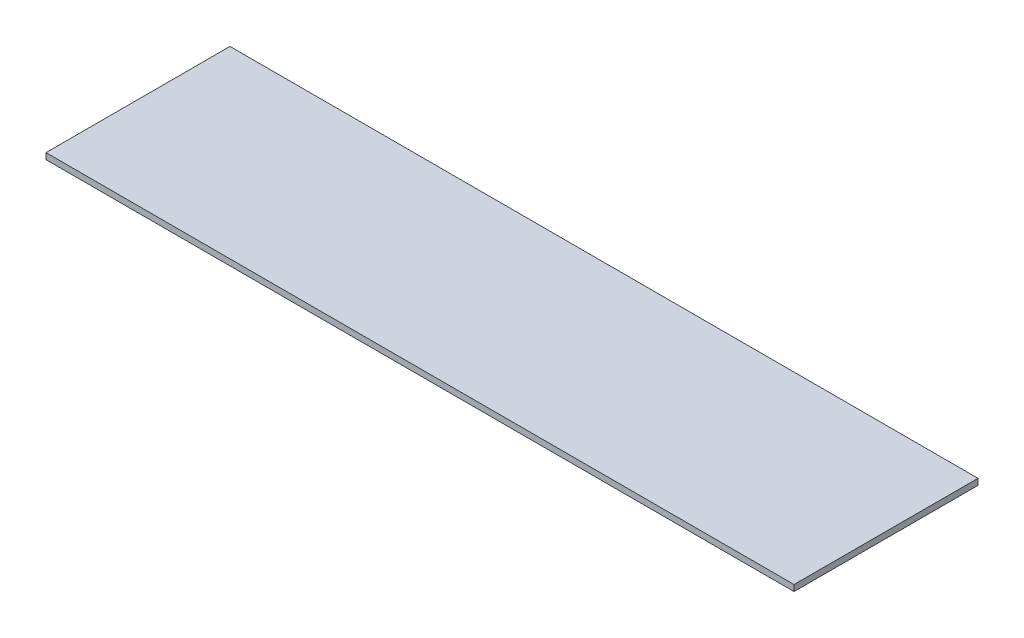
SolidWorks part; units mm, degrees
ref_plane "Front Plane" through (0, 0, 0) normal (0, 0, 1) x (1, 0, 0)
ref_plane "Top Plane" through (0, 0, 0) normal (0, 1, 0) x (1, 0, 0)
ref_plane "Right Plane" through (0, 0, 0) normal (1, 0, 0) x (0, 0, -1)
sketch "Sketch1" plane through (0, 0, 0) normal (0, 1, 0) x (1, 0, 0)
  line L0 (0, 88.9) -> (0, -88.9) construction
  line L1 (-381, 88.9) -> (381, 88.9)
  line L2 (-381, 88.9) -> (-381, -88.9)
  line L3 (-381, -88.9) -> (381, -88.9)
  line L4 (381, 88.9) -> (381, -88.9)
  line L5 (-381, 39.4607) -> (-381, 65.7679)
  line L7 (-381, 65.7679) -> (-381, 88.9)
  line L14 (-325.0712, -88.9) -> (-381, -88.9)
  line L19 (381, 65.7679) -> (381, 88.9)
  line L22 (-325.0712, 88.9) -> (-381, 88.9)
  line L29 (381, 39.4607) -> (381, 65.7679)
  line L33 (-381, 13.1536) -> (-381, 39.4607)
  line L37 (381, 13.1536) -> (381, 39.4607)
  line L41 (-381, -13.1536) -> (-381, 13.1536)
  line L45 (381, -13.1536) -> (381, 13.1536)
  line L49 (-381, -39.4607) -> (-381, -13.1536)
  line L53 (381, -39.4607) -> (381, -13.1536)
  line L57 (-381, -65.7679) -> (-381, -39.4607)
  line L61 (381, -65.7679) -> (381, -39.4607)
  line L65 (-381, -88.9) -> (-381, -65.7679)
  line L69 (381, -88.9) -> (381, -65.7679)
  line L74 (-265.9673, -88.9) -> (-325.0712, -88.9)
  line L78 (-265.9673, 88.9) -> (-325.0712, 88.9)
  line L82 (-206.8635, -88.9) -> (-265.9673, -88.9)
  line L86 (-206.8635, 88.9) -> (-265.9673, 88.9)
  line L90 (-147.7596, -88.9) -> (-206.8635, -88.9)
  line L93 (-147.7596, 88.9) -> (-147.7596, 92.075)
  line L94 (-147.7596, 88.9) -> (-206.8635, 88.9)
  line L98 (-88.6558, -88.9) -> (-147.7596, -88.9)
  line L102 (-88.6558, 88.9) -> (-147.7596, 88.9)
  line L103 (-147.7596, 88.9) -> (-147.7596, 92.075)
  line L105 (-29.5519, -88.9) -> (-29.5519, -92.075)
  line L106 (-29.5519, -88.9) -> (-88.6558, -88.9)
  line L110 (-29.5519, 88.9) -> (-88.6558, 88.9)
  line L114 (29.5519, -88.9) -> (-29.5519, -88.9)
  line L115 (-29.5519, -88.9) -> (-29.5519, -92.075)
  line L118 (29.5519, 88.9) -> (-29.5519, 88.9)
  line L122 (88.6558, -88.9) -> (29.5519, -88.9)
  line L126 (88.6558, 88.9) -> (29.5519, 88.9)
  line L130 (147.7596, -88.9) -> (88.6558, -88.9)
  line L134 (147.7596, 88.9) -> (88.6558, 88.9)
  line L138 (206.8635, -88.9) -> (147.7596, -88.9)
  line L142 (206.8635, 88.9) -> (147.7596, 88.9)
  line L146 (265.9673, -88.9) -> (206.8635, -88.9)
  line L150 (265.9673, 88.9) -> (206.8635, 88.9)
  line L186 (325.0712, -88.9) -> (265.9673, -88.9)
  line L190 (325.0712, 88.9) -> (265.9673, 88.9)
  line L194 (381, -88.9) -> (325.0712, -88.9)
  line L198 (381, 88.9) -> (325.0712, 88.9)
  point P8 (0, 88.9)
  point P9 (0, 0)
  dimension "D1" = 762
  dimension "D2" = 177.8
  dimension "D4" = 7
  dimension "D7" = 13
extrude "Boss-Extrude1" add sketch "Sketch1" along normal blind 6.35
sketch "Sketch4" [suppressed] plane through (0, 0, 0) normal (0, 1, 0) x (1, 0, 0)
  line L0 (0.0158, 88.9) -> (0.0158, -88.9) construction
  line L1 (-380.9842, 88.9) -> (381.0158, 88.9)
  line L2 (-380.9842, 88.9) -> (-380.9842, -88.9)
  line L3 (-380.9842, -88.9) -> (381.0158, -88.9)
  line L4 (381.0158, 88.9) -> (381.0158, -88.9)
  line L5 (-381, 39.4607) -> (-381, 65.7679)
  line L6 (-380.9842, 65.7679) -> (-384.1592, 65.7679)
  line L7 (-380.9842, 65.7679) -> (-380.9842, 92.075)
  line L8 (-380.9842, 92.075) -> (-384.1592, 92.075)
  line L9 (-384.1592, 65.7679) -> (-384.1592, 92.075)
  line L10 (-325.0554, -88.9) -> (-384.1592, -88.9)
  line L11 (-325.0554, -88.9) -> (-325.0554, -92.075)
  line L12 (-325.0554, -92.075) -> (-384.1592, -92.075)
  line L13 (-384.1592, -88.9) -> (-384.1592, -92.075)
  line L14 (381.0158, 65.7679) -> (384.1908, 65.7679)
  line L15 (381.0158, 65.7679) -> (381.0158, 92.075)
  line L16 (381.0158, 92.075) -> (384.1908, 92.075)
  line L17 (384.1908, 65.7679) -> (384.1908, 92.075)
  line L18 (-325.0554, 88.9) -> (-384.1592, 88.9)
  line L19 (-325.0554, 88.9) -> (-325.0554, 92.075)
  line L20 (-325.0554, 92.075) -> (-384.1592, 92.075)
  line L21 (-384.1592, 88.9) -> (-384.1592, 92.075)
  line L22 (-381, 39.4607) -> (-384.175, 39.4607)
  line L23 (-384.175, 39.4607) -> (-384.1592, 65.7679)
  line L24 (-381, 65.7679) -> (-384.1592, 65.7679)
  line L25 (381, 39.4607) -> (381, 65.7679)
  line L26 (381, 39.4607) -> (384.175, 39.4607)
  line L27 (384.175, 39.4607) -> (384.175, 65.7679)
  line L28 (381, 65.7679) -> (384.175, 65.7679)
  line L29 (-381, 13.1536) -> (-381, 39.4607)
  line L30 (-381, 13.1536) -> (-384.175, 13.1536)
  line L31 (-384.175, 13.1536) -> (-384.175, 39.4607)
  line L32 (-381, 39.4607) -> (-384.175, 39.4607)
  line L33 (381, 13.1536) -> (381, 39.4607)
  line L34 (381, 13.1536) -> (384.175, 13.1536)
  line L35 (384.175, 13.1536) -> (384.175, 39.4607)
  line L36 (381, 39.4607) -> (384.175, 39.4607)
  line L37 (-381, -13.1536) -> (-381, 13.1536)
  line L38 (-381, -13.1536) -> (-384.175, -13.1536)
  line L39 (-384.175, -13.1536) -> (-384.175, 13.1536)
  line L40 (-381, 13.1536) -> (-384.175, 13.1536)
  line L41 (381, -13.1536) -> (381, 13.1536)
  line L42 (381, -13.1536) -> (384.175, -13.1536)
  line L43 (384.175, -13.1536) -> (384.175, 13.1536)
  line L44 (381, 13.1536) -> (384.175, 13.1536)
  line L45 (-381, -39.4607) -> (-381, -13.1536)
  line L46 (-381, -39.4607) -> (-384.175, -39.4607)
  line L47 (-384.175, -39.4607) -> (-384.175, -13.1536)
  line L48 (-381, -13.1536) -> (-384.175, -13.1536)
  line L49 (381, -39.4607) -> (381, -13.1536)
  line L50 (381, -39.4607) -> (384.175, -39.4607)
  line L51 (384.175, -39.4607) -> (384.175, -13.1536)
  line L52 (381, -13.1536) -> (384.175, -13.1536)
  line L53 (-381, -65.7679) -> (-381, -39.4607)
  line L54 (-381, -65.7679) -> (-384.175, -65.7679)
  line L55 (-384.175, -65.7679) -> (-384.175, -39.4607)
  line L56 (-381, -39.4607) -> (-384.175, -39.4607)
  line L57 (381, -65.7679) -> (381, -39.4607)
  line L58 (381, -65.7679) -> (384.175, -65.7679)
  line L59 (384.175, -65.7679) -> (384.175, -39.4607)
  line L60 (381, -39.4607) -> (384.175, -39.4607)
  line L61 (-381, -92.075) -> (-381, -65.7679)
  line L62 (-381, -92.075) -> (-384.175, -92.075)
  line L63 (-384.175, -92.075) -> (-384.175, -65.7679)
  line L64 (-381, -65.7679) -> (-384.175, -65.7679)
  line L65 (381, -92.075) -> (381, -65.7679)
  line L66 (381, -92.075) -> (384.175, -92.075)
  line L67 (384.175, -92.075) -> (384.175, -65.7679)
  line L68 (381, -65.7679) -> (384.175, -65.7679)
  line L69 (-265.9673, -88.9) -> (-265.9673, -92.075)
  line L70 (-265.9673, -88.9) -> (-325.0554, -88.9)
  line L71 (-325.0554, -88.9) -> (-325.0554, -92.075)
  line L72 (-265.9673, -92.075) -> (-325.0554, -92.075)
  line L73 (-265.9673, 88.9) -> (-265.9673, 92.075)
  line L74 (-265.9673, 88.9) -> (-325.0712, 88.9)
  line L75 (-325.0712, 88.9) -> (-325.0712, 92.075)
  line L76 (-265.9673, 92.075) -> (-325.0712, 92.075)
  line L77 (-206.8635, -88.9) -> (-206.8635, -92.075)
  line L78 (-206.8635, -88.9) -> (-265.9673, -88.9)
  line L79 (-265.9673, -88.9) -> (-265.9673, -92.075)
  line L80 (-206.8635, -92.075) -> (-265.9673, -92.075)
  line L81 (-206.8635, 88.9) -> (-206.8635, 92.075)
  line L82 (-206.8635, 88.9) -> (-265.9673, 88.9)
  line L83 (-265.9673, 88.9) -> (-265.9673, 92.075)
  line L84 (-206.8635, 92.075) -> (-265.9673, 92.075)
  line L85 (-147.7596, -88.9) -> (-147.7596, -92.075)
  line L86 (-147.7596, -88.9) -> (-206.8635, -88.9)
  line L87 (-206.8635, -88.9) -> (-206.8635, -92.075)
  line L88 (-147.7596, -92.075) -> (-206.8635, -92.075)
  line L89 (-147.7596, 88.9) -> (-147.7596, 92.075)
  line L90 (-147.7596, 88.9) -> (-206.8635, 88.9)
  line L91 (-206.8635, 88.9) -> (-206.8635, 92.075)
  line L92 (-147.7596, 92.075) -> (-206.8635, 92.075)
  line L93 (-88.6558, -88.9) -> (-88.6558, -92.075)
  line L94 (-88.6558, -88.9) -> (-147.7596, -88.9)
  line L95 (-147.7596, -88.9) -> (-147.7596, -92.075)
  line L96 (-88.6558, -92.075) -> (-147.7596, -92.075)
  line L97 (-88.6558, 88.9) -> (-88.6558, 92.075)
  line L98 (-88.6558, 88.9) -> (-147.7596, 88.9)
  line L99 (-147.7596, 88.9) -> (-147.7596, 92.075)
  line L100 (-88.6558, 92.075) -> (-147.7596, 92.075)
  line L101 (-29.5519, -88.9) -> (-29.5519, -92.075)
  line L102 (-29.5519, -88.9) -> (-88.6558, -88.9)
  line L103 (-88.6558, -88.9) -> (-88.6558, -92.075)
  line L104 (-29.5519, -92.075) -> (-88.6558, -92.075)
  line L105 (-29.5519, 88.9) -> (-29.5519, 92.075)
  line L106 (-29.5519, 88.9) -> (-88.6558, 88.9)
  line L107 (-88.6558, 88.9) -> (-88.6558, 92.075)
  line L108 (-29.5519, 92.075) -> (-88.6558, 92.075)
  line L109 (29.5519, -88.9) -> (29.5519, -92.075)
  line L110 (29.5519, -88.9) -> (-29.5519, -88.9)
  line L111 (-29.5519, -88.9) -> (-29.5519, -92.075)
  line L112 (29.5519, -92.075) -> (-29.5519, -92.075)
  line L113 (29.5519, 88.9) -> (29.5519, 92.075)
  line L114 (29.5519, 88.9) -> (-29.5519, 88.9)
  line L115 (-29.5519, 88.9) -> (-29.5519, 92.075)
  line L116 (29.5519, 92.075) -> (-29.5519, 92.075)
  line L117 (88.6558, -88.9) -> (88.6558, -92.075)
  line L118 (88.6558, -88.9) -> (29.5519, -88.9)
  line L119 (29.5519, -88.9) -> (29.5519, -92.075)
  line L120 (88.6558, -92.075) -> (29.5519, -92.075)
  line L121 (88.6558, 88.9) -> (88.6558, 92.075)
  line L122 (88.6558, 88.9) -> (29.5519, 88.9)
  line L123 (29.5519, 88.9) -> (29.5519, 92.075)
  line L124 (88.6558, 92.075) -> (29.5519, 92.075)
  line L125 (147.7596, -88.9) -> (147.7596, -92.075)
  line L126 (147.7596, -88.9) -> (88.6558, -88.9)
  line L127 (88.6558, -88.9) -> (88.6558, -92.075)
  line L128 (147.7596, -92.075) -> (88.6558, -92.075)
  line L129 (147.7596, 88.9) -> (147.7596, 92.075)
  line L130 (147.7596, 88.9) -> (88.6558, 88.9)
  line L131 (88.6558, 88.9) -> (88.6558, 92.075)
  line L132 (147.7596, 92.075) -> (88.6558, 92.075)
  line L133 (206.8635, -88.9) -> (206.8635, -92.075)
  line L134 (206.8635, -88.9) -> (147.7596, -88.9)
  line L135 (147.7596, -88.9) -> (147.7596, -92.075)
  line L136 (206.8635, -92.075) -> (147.7596, -92.075)
  line L137 (206.8635, 88.9) -> (206.8635, 92.075)
  line L138 (206.8635, 88.9) -> (147.7596, 88.9)
  line L139 (147.7596, 88.9) -> (147.7596, 92.075)
  line L140 (206.8635, 92.075) -> (147.7596, 92.075)
  line L141 (265.9673, -88.9) -> (265.9673, -92.075)
  line L142 (265.9673, -88.9) -> (206.8635, -88.9)
  line L143 (206.8635, -88.9) -> (206.8635, -92.075)
  line L144 (265.9673, -92.075) -> (206.8635, -92.075)
  line L145 (265.9673, 88.9) -> (265.9673, 92.075)
  line L146 (265.9673, 88.9) -> (206.8635, 88.9)
  line L147 (206.8635, 88.9) -> (206.8635, 92.075)
  line L148 (265.9673, 92.075) -> (206.8635, 92.075)
  line L149 (325.0712, -88.9) -> (325.0712, -92.075)
  line L150 (325.0712, -88.9) -> (265.9673, -88.9)
  line L151 (265.9673, -88.9) -> (265.9673, -92.075)
  line L152 (325.0712, -92.075) -> (265.9673, -92.075)
  line L153 (325.0712, 88.9) -> (325.0712, 92.075)
  line L154 (325.0712, 88.9) -> (265.9673, 88.9)
  line L155 (265.9673, 88.9) -> (265.9673, 92.075)
  line L156 (325.0712, 92.075) -> (265.9673, 92.075)
  line L157 (384.175, -88.9) -> (384.175, -92.075)
  line L158 (384.175, -88.9) -> (325.0712, -88.9)
  line L159 (325.0712, -88.9) -> (325.0712, -92.075)
  line L160 (384.175, -92.075) -> (325.0712, -92.075)
  line L161 (384.175, 88.9) -> (384.175, 92.075)
  line L162 (384.175, 88.9) -> (325.0712, 88.9)
  line L163 (325.0712, 88.9) -> (325.0712, 92.075)
  line L164 (384.175, 92.075) -> (325.0712, 92.075)
  point P7 (0.0158, 88.9)
  dimension "D1" = 762
  dimension "D2" = 177.8
  dimension "D3" = 184.15
  dimension "D4" = 768.35
  dimension "D5" = 26.3071
  dimension "D6" = 59.1038
sketch "Sketch2" plane through (0, 6.35, 0) normal (0, 1, 0) x (1, 0, 0)
  line L0 (-123.825, 0) -> (123.825, 0) construction
  line L1 (-130.175, 15.4404) -> (-123.825, 15.4404) construction
  line L2 (-130.175, 15.4404) -> (-130.175, -15.4404) construction
  line L3 (-130.175, -15.4404) -> (-123.825, -15.4404) construction
  line L4 (-123.825, 15.4404) -> (-123.825, -15.4404) construction
  line L5 (123.825, 14.3164) -> (130.175, 14.3164) construction
  line L6 (123.825, 14.3164) -> (123.825, -14.3164) construction
  line L7 (123.825, -14.3164) -> (130.175, -14.3164) construction
  line L8 (130.175, 14.3164) -> (130.175, -14.3164) construction
  line L9 (-130.9687, 24.6215) -> (-123.0313, 24.6215) construction
  line L10 (-127, 24.6215) -> (-127, 15.4404) construction
  line L12 (-123.0312, 76.2) -> (-116.6812, 76.2)
  line L13 (-123.0312, 76.2) -> (-123.0313, 88.9)
  line L14 (-123.0313, 88.9) -> (-116.6812, 88.9)
  line L15 (-116.6812, 76.2) -> (-116.6812, 88.9)
  line L16 (-123.0313, 24.6215) -> (-123.0312, 76.2) construction
  line L18 (-116.6812, -88.9) -> (-123.0313, -88.9)
  line L19 (-116.6812, -88.9) -> (-116.6812, -76.2)
  line L20 (-116.6812, -76.2) -> (-123.0313, -76.2)
  line L21 (-123.0313, -88.9) -> (-123.0313, -76.2)
  line L31 (-381, 88.9) -> (381, 88.9) construction
  line L32 (-381, -88.9) -> (381, -88.9) construction
  line L33 (130.9688, 76.2) -> (130.9688, 88.9)
  line L34 (130.9688, 76.2) -> (137.3188, 76.2)
  line L35 (137.3188, 76.2) -> (137.3188, 88.9)
  line L36 (130.9688, 88.9) -> (137.3188, 88.9)
  line L37 (137.3188, -88.9) -> (137.3188, -76.2)
  line L38 (137.3188, -88.9) -> (130.9688, -88.9)
  line L39 (130.9688, -88.9) -> (130.9688, -76.2)
  line L40 (137.3188, -76.2) -> (130.9688, -76.2)
  line L41 (123.0313, 24.6215) -> (130.9688, 24.6215) construction
  line L42 (127, 24.6215) -> (127, 14.3164) construction
  line L43 (130.9688, 24.6215) -> (130.9688, 76.2) construction
  point P10 (0, 0)
  point P43 (127, 14.3164)
  dimension "D1" = 6.35
  dimension "D2" = 7.9375
  dimension "D4" = 6.35
  dimension "D5" = 12.7
  dimension "D3" = 254
  dimension "D6" = 2
extrude "Cut-Extrude1" [suppressed] cut sketch "Sketch2" against normal through all
sketch "Sketch5" plane through (0, 6.35, 0) normal (0, 1, 0) x (1, 0, 0)
  line L0 (-381, 88.9) -> (-381, -88.9) construction
  line L1 (-387.35, 95.25) -> (387.35, 95.25)
  line L2 (-387.35, 95.25) -> (-387.35, -95.25)
  line L3 (-387.35, -95.25) -> (387.35, -95.25)
  line L4 (387.35, 95.25) -> (387.35, -95.25)
  line L5 (-381, -88.9) -> (381, -88.9) construction
  line L7 (-381, 88.9) -> (381, 88.9)
  line L8 (-381, 88.9) -> (-381, -88.9)
  line L9 (-381, -88.9) -> (381, -88.9)
  line L10 (381, 88.9) -> (381, -88.9)
  dimension "D1" = 774.7
  dimension "D2" = 190.5
  dimension "D3" = 6.35
  dimension "0.25" = 6.35
extrude "Boss-Extrude2" add sketch "Sketch5" against normal up to surface (6.35 mm away) up to face at (0, 0, 0)
equation "\"Height\"= 12in"
equation "\"Depth\"= 7in"
equation "\"WallThickness\"= 0.25in"
equation "\"FloorThickness\"= 0.25in"
equation "\"D1@Sketch1\"=\"Width\""
equation "\"D2@Sketch1\"=\"Depth\""
equation "\"D1@Boss-Extrude1\"=\"FloorThickness\""
equation "\"D1@Sketch2\"=\"WallThickness\""
equation "\"D2@Sketch2\"=\"WallThickness\"+(1/16in)"
equation "\"D4@Sketch2\"=\"WallThickness\""
equation "\"Width\" = 30in"
